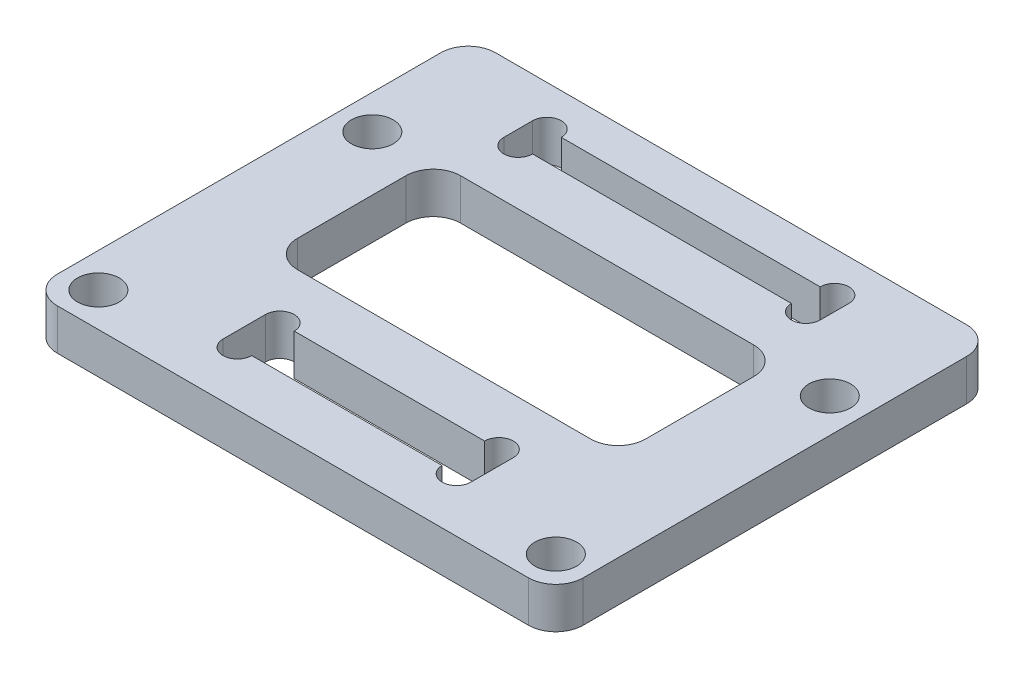
SolidWorks part; units mm, degrees
material "Thornel Mat VMA"
ref_plane "前视基准面" through (0, 0, 0) normal (0, 0, 1) x (1, 0, 0)
ref_plane "上视基准面" through (0, 0, 0) normal (0, 1, 0) x (1, 0, 0)
ref_plane "右视基准面" through (0, 0, 0) normal (1, 0, 0) x (0, 0, -1)
other "Configuration Table"
sketch "草图1" plane through (0, 0, 0) normal (0, 1, 0) x (1, 0, 0)
  line L1 (-19.2, -16) -> (19.2, -16)
  line L2 (-19.2, -16) -> (-19.2, 16)
  line L3 (-19.2, 16) -> (19.2, 16)
  line L4 (19.2, -16) -> (19.2, 16)
  line L5 (-19.2, -16) -> (19.2, 16) construction
  line L6 (-19.2, 16) -> (19.2, -16) construction
  point P0 (0, 0)
  dimension "D1" = 38.4
  dimension "D2" = 32
extrude "凸台-拉伸1" add sketch "草图1" along normal blind 3
sketch "草图2" plane through (0, 0, 0) normal (0, -1, 0) x (1, 0, 0)
  line L0 (-16.7, 13.5) -> (-16.7, -6.5) construction
  line L1 (-16.7, -6.5) -> (16.7, -6.5) construction
  line L2 (16.7, -6.5) -> (16.7, 13.5) construction
  circle A0 centre (-16.7, 13.5) radius 1.25 construction
  circle A1 centre (-16.7, 13.5) radius 1.25 construction
  circle A2 centre (16.7, 13.5) radius 1.25 construction
  circle A3 centre (16.7, 13.5) radius 1.25 construction
  circle A4 centre (-16.7, 13.5) radius 1.525
  circle A5 centre (16.7, 13.5) radius 1.525
  circle A6 centre (-16.7, -6.5) radius 1.525
  circle A7 centre (16.7, -6.5) radius 1.525
  dimension "D1" = 3.05
  dimension "D2" = 20
extrude "切除-拉伸1" cut sketch "草图2" against normal blind 3
sketch "草图3" plane through (0, 0, 0) normal (0, -1, 0) x (1, 0, 0)
  line L0 (11.55, -10.95) -> (-11.55, -10.95)
  line L1 (-11.55, -10.95) -> (-11.55, -13.05)
  line L2 (-11.55, -13.05) -> (11.55, -13.05)
  line L3 (11.55, -13.05) -> (11.55, -10.95)
  line L4 (11.5, -11) -> (-11.5, -11)
  line L5 (-11.5, -11) -> (-11.5, -13)
  line L6 (-11.5, -13) -> (11.5, -13)
  line L7 (11.5, -13) -> (11.5, -11)
  line L8 (11.5, -11) -> (-11.5, -11) construction
  line L9 (-11.5, -11) -> (-11.5, -13) construction
  line L10 (-11.5, -13) -> (11.5, -13) construction
  line L11 (11.5, -13) -> (11.5, -11) construction
  dimension "D1" = 0
  dimension "D2" = 0.05
extrude "切除-拉伸2" cut sketch "草图3" against normal up to surface (3 mm away) up to face at (16.7, 3, 11.975)
sketch "草图4" plane through (0, 0, 0) normal (0, -1, 0) x (1, 0, 0)
  line L1 (11.55, -10.95) -> (-11.55, -10.95) construction
  line L2 (-11.55, -13.05) -> (11.55, -13.05) construction
  circle A1 centre (10.5, -10.95) radius 1.05
  circle A2 centre (10.5, -13.05) radius 1.05
  circle A3 centre (-10.5, -13.05) radius 1.05
  circle A4 centre (-10.5, -10.95) radius 1.05
  line M2 (11.55, -13.05) -> (-11.55, -13.05)
  line M4 (-11.55, -10.95) -> (11.55, -10.95)
  dimension "D1" = 2.1
extrude "切除-拉伸3" cut sketch "草图4" against normal up to surface (3 mm away) contours A3 M2 | A4 M4 | A1 M4 | A2 M2 up to face at (0, 3, -12)
sketch "草图5" plane through (0, 0, 0) normal (0, -1, 0) x (1, 0, 0)
  line L0 (9.05, 12.05) -> (-9.05, 12.05)
  line L1 (-9.05, 12.05) -> (-9.05, 8.95)
  line L2 (-9.05, 8.95) -> (9.05, 8.95)
  line L3 (9.05, 8.95) -> (9.05, 12.05)
  line L4 (9, 12) -> (-9, 12)
  line L5 (-9, 12) -> (-9, 9)
  line L6 (-9, 9) -> (9, 9)
  line L7 (9, 9) -> (9, 12)
  line L8 (9, 12) -> (-9, 12) construction
  line L9 (-9, 12) -> (-9, 9) construction
  line L10 (-9, 9) -> (9, 9) construction
  line L11 (9, 9) -> (9, 12) construction
  dimension "D1" = 0
  dimension "D2" = 0.05
extrude "切除-拉伸4" cut sketch "草图5" against normal up to surface (3 mm away) up to face at (0, 3, -12)
sketch "草图6" plane through (0, 0, 0) normal (0, -1, 0) x (1, 0, 0)
  line L0 (-9.05, 8.95) -> (9.05, 8.95) construction
  line L1 (9.05, 12.05) -> (-9.05, 12.05) construction
  circle A0 centre (-8, 8.95) radius 1.05
  circle A1 centre (-8, 12.05) radius 1.05
  circle A2 centre (8, 12.05) radius 1.05
  circle A4 centre (8, 8.95) radius 1.05
  dimension "D1" = 2.1
extrude "切除-拉伸5" cut sketch "草图6" against normal up to surface (3 mm away) up to face at (0, 3, 10.5)
sketch "草图7" plane through (0, 3, 0) normal (0, 1, 0) x (1, 0, 0)
  line L0 (-9.45, 10.95) -> (9.45, 10.95) construction
  line L1 (-12.7, -4.95) -> (12.7, -4.95)
  line L2 (-12.7, -4.95) -> (-12.7, 6.95)
  line L3 (-12.7, 6.95) -> (12.7, 6.95)
  line L4 (12.7, -4.95) -> (12.7, 6.95)
  line L5 (-12.7, -4.95) -> (12.7, 6.95) construction
  line L6 (-12.7, 6.95) -> (12.7, -4.95) construction
  line L7 (6.95, -8.95) -> (-6.95, -8.95) construction
  circle A0 centre (-16.7, 6.5) radius 1.525 construction
  circle A1 centre (16.7, 6.5) radius 1.525 construction
  point P0 (0, 1)
  dimension "D1" = 4
  dimension "D2" = 4
  dimension "D3" = 4
  dimension "D4" = 4
extrude "切除-拉伸6" cut sketch "草图7" against normal up to surface (3 mm away) up to face at (0, 0, 10.5)
fillet "圆角1" radius 2 4 edges at (12.7, 1.5, -6.95) (-12.7, 1.5, -6.95) (-12.7, 1.5, 4.95) (12.7, 1.5, 4.95)
fillet "圆角2" radius 2 4 edges at (19.2, 1.5, 16) (-19.2, 1.5, 16) (-19.2, 1.5, -16) (19.2, 1.5, -16)
